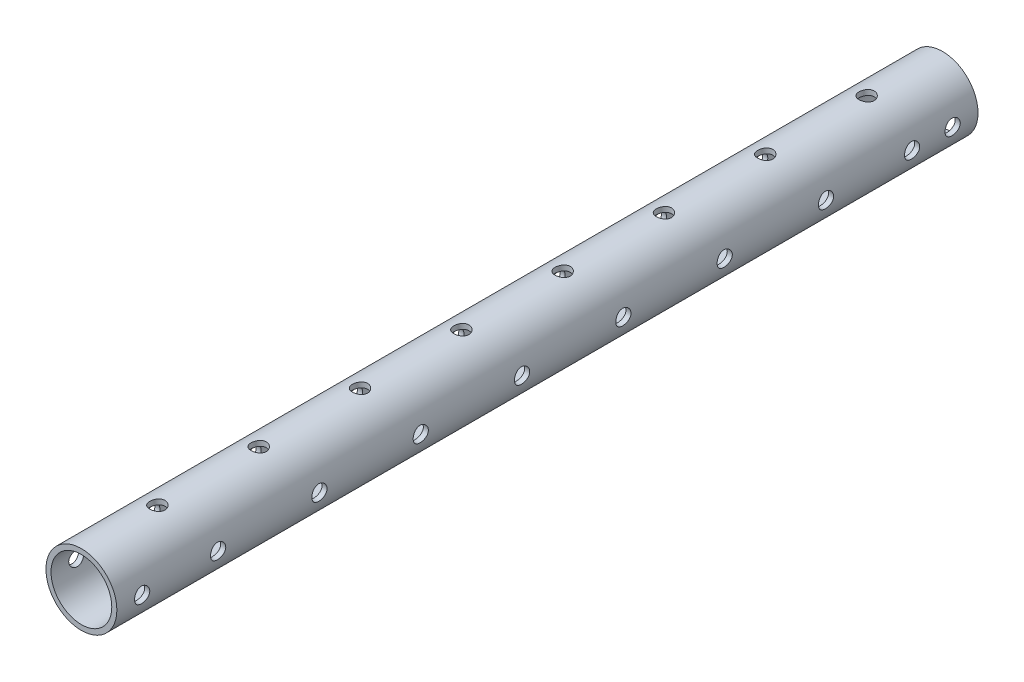
SolidWorks part; units mm, degrees
material "Thornel Mat VMA"
ref_plane "前视基准面" through (0, 0, 0) normal (0, 0, 1) x (1, 0, 0)
ref_plane "上视基准面" through (0, 0, 0) normal (0, 1, 0) x (1, 0, 0)
ref_plane "右视基准面" through (0, 0, 0) normal (1, 0, 0) x (0, 0, -1)
sketch "草图1" plane through (0, 0, 0) normal (0, 0, 1) x (1, 0, 0)
  circle A0 centre (0, 0) radius 7
  circle A1 centre (0, 0) radius 6
  dimension "D1" = 12
  dimension "D2" = 14
extrude "凸台-拉伸1" add sketch "草图1" along normal blind 170
sketch "草图3" plane through (0, 0, 0) normal (1, 0, 0) x (0, 0, -1)
  line L0 (-170, 7) -> (-170, -7) construction
  line L1 (0, -7) -> (0, 7) construction
  line L2 (-170, 0) -> (11.2928, 0) construction
  line L3 (-30, 0) -> (-50, 0) construction
  circle A0 centre (-165, 0) radius 1.5
  circle A1 centre (-5, 0) radius 1.5
  circle A2 centre (-13, 0) radius 1.5
  circle A3 centre (-30, 0) radius 1.5
  circle A4 centre (-50, 0) radius 1.5
  circle A5 centre (-70, 0) radius 1.5
  circle A6 centre (-90, 0) radius 1.5
  circle A7 centre (-110, 0) radius 1.5
  circle A8 centre (-130, 0) radius 1.5
  circle A9 centre (-150, 0) radius 1.5
  dimension "D1" = 3
  dimension "D2" = 5
  dimension "D3" = 5
  dimension "D4" = 8
  dimension "D5" = 30
  dimension "D9" = 3
  dimension "D7" = 20
  dimension "D6" = 6
  dimension "D8" = 2
extrude "切除-拉伸1" cut sketch "草图3" against normal through all both and the other way through all
sketch "草图4" plane through (0, 0, 0) normal (0, 1, 0) x (1, 0, 0)
  line L0 (0, 0) -> (0, -162.1478) construction
  line L1 (6, 0) -> (-6, 0) construction
  circle A0 centre (0, -15) radius 1.5
  circle A1 centre (0, -35) radius 1.5
  circle A2 centre (0, -55) radius 1.5
  circle A3 centre (0, -75) radius 1.5
  circle A4 centre (0, -95) radius 1.5
  circle A5 centre (0, -115) radius 1.5
  circle A6 centre (0, -135) radius 1.5
  circle A7 centre (0, -155) radius 1.5
  dimension "D1" = 3
  dimension "D2" = 15
  dimension "D3" = 7
  dimension "D4" = 2
extrude "切除-拉伸2" cut sketch "草图4" against normal through all both and the other way through all
